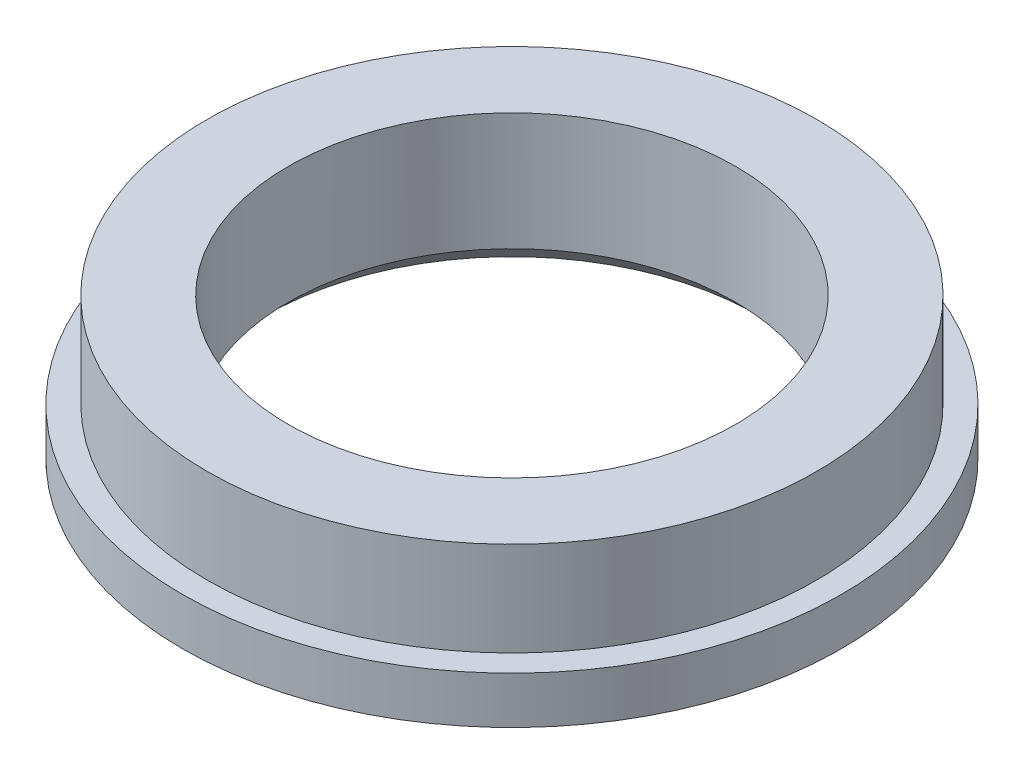
SolidWorks part; units mm, degrees
ref_plane "Front Plane" through (0, 0, 0) normal (0, 0, 1) x (1, 0, 0)
ref_plane "Top Plane" through (0, 0, 0) normal (0, 1, 0) x (1, 0, 0)
ref_plane "Right Plane" through (0, 0, 0) normal (1, 0, 0) x (0, 0, -1)
sketch "Sketch1" plane through (0, 0, 0) normal (0, 1, 0) x (1, 0, 0)
  circle A0 centre (0, 0) radius 7
  dimension "D1" = 14
extrude "Boss-Extrude1" add sketch "Sketch1" along normal blind 1
sketch "Sketch2" plane through (0, 1, 0) normal (0, 1, 0) x (1, 0, 0)
  circle A0 centre (0, 0) radius 6.475
  dimension "D1" = 12.95
extrude "Boss-Extrude2" add sketch "Sketch2" along normal blind 2
sketch "Sketch3" plane through (0, 0, 0) normal (0, -1, 0) x (1, 0, 0)
  circle A0 centre (0, 0) radius 4.75
  dimension "D1" = 9.5
extrude "Cut-Extrude1" cut sketch "Sketch3" against normal through all
chamfer "Chamfer1" distance 0.5 angle 45 1 edges at (0, 0, -4.75)
